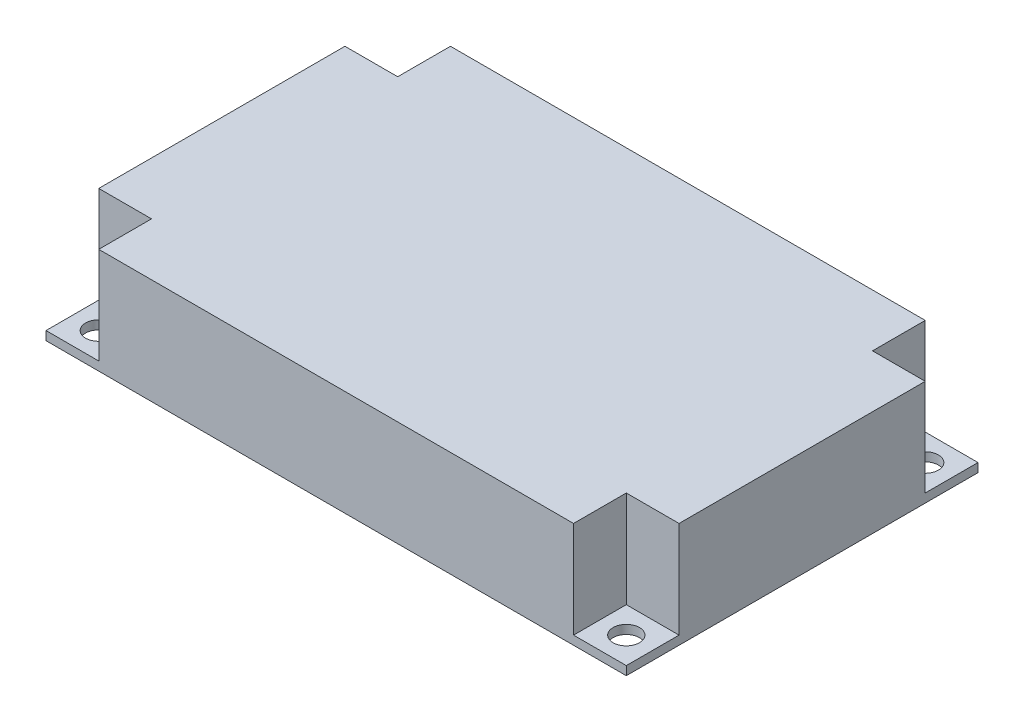
SolidWorks part; units mm, degrees
ref_plane "前视基准面" through (0, 0, 0) normal (0, 0, 1) x (1, 0, 0)
ref_plane "上视基准面" through (0, 0, 0) normal (0, 1, 0) x (1, 0, 0)
ref_plane "右视基准面" through (0, 0, 0) normal (1, 0, 0) x (0, 0, -1)
sketch "草图1" plane through (0, 0, 0) normal (0, 1, 0) x (1, 0, 0)
  line L1 (-33, -20) -> (33, -20)
  line L2 (-33, -20) -> (-33, 20)
  line L3 (-33, 20) -> (33, 20)
  line L4 (33, -20) -> (33, 20)
  line L5 (-33, -20) -> (33, 20) construction
  line L6 (-33, 20) -> (33, -20) construction
  point P0 (0, 0)
  dimension "D1" = 40
  dimension "D2" = 66
extrude "凸台-拉伸1" add sketch "草图1" along normal blind 12
sketch "草图2" plane through (0, 12, 0) normal (0, 1, 0) x (1, 0, 0)
  line L0 (-42.0466, 0) -> (47.0346, 0) construction
  line L1 (0, 25.7478) -> (0, -23.289) construction
  line L2 (-33, 20) -> (-33, -20) construction
  line L3 (-33, -20) -> (33, -20) construction
  circle A0 centre (-30, -17) radius 1.5
  circle A1 centre (30, -17) radius 1.5
  circle A2 centre (30, 17) radius 1.5
  circle A3 centre (-30, 17) radius 1.5
  dimension "D1" = 3
  dimension "D2" = 3
  dimension "D3" = 3
extrude "切除-拉伸1" cut sketch "草图2" against normal through all
sketch "草图3" plane through (0, 12, 0) normal (0, 1, 0) x (1, 0, 0)
  line L5 (-33, 20) -> (-27, 20)
  line L6 (-33, 20) -> (-33, 14)
  line L7 (-33, 14) -> (-27, 14)
  line L8 (-27, 20) -> (-27, 14)
  line L9 (33, 20) -> (27, 20)
  line L10 (33, 20) -> (33, 14)
  line L11 (33, 14) -> (27, 14)
  line L12 (27, 20) -> (27, 14)
  line L13 (33, -20) -> (27, -20)
  line L14 (33, -20) -> (33, -14)
  line L15 (33, -14) -> (27, -14)
  line L16 (27, -20) -> (27, -14)
  line L17 (-33, -20) -> (-27, -20)
  line L18 (-33, -20) -> (-33, -14)
  line L19 (-33, -14) -> (-27, -14)
  line L20 (-27, -20) -> (-27, -14)
  dimension "D1" = 6
  dimension "D2" = 6
  dimension "D3" = 6
  dimension "D4" = 6
  dimension "D5" = 6
  dimension "D6" = 6
  dimension "D7" = 6
  dimension "D8" = 6
extrude "切除-拉伸2" cut sketch "草图3" against normal blind 11
